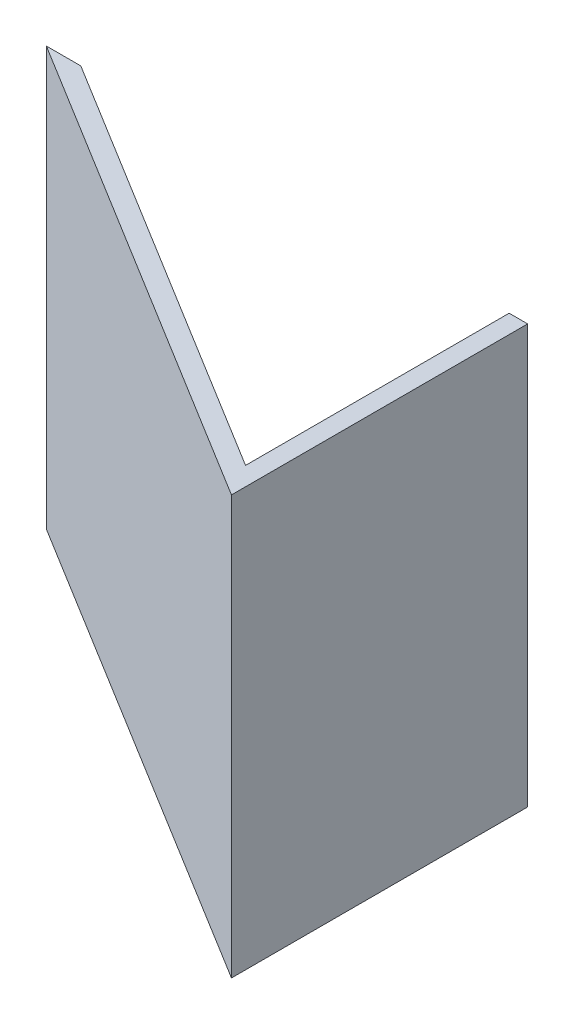
SolidWorks part; units mm, degrees
ref_plane "Front Plane" through (0, 0, 0) normal (0, 0, 1) x (1, 0, 0)
ref_plane "Top Plane" through (0, 0, 0) normal (0, 1, 0) x (1, 0, 0)
ref_plane "Right Plane" through (0, 0, 0) normal (1, 0, 0) x (0, 0, -1)
sketch "Sketch1" plane through (0, 0, 0) normal (0, 1, 0) x (1, 0, 0)
  line L1 (65.0271, 34.1908) -> (65.0271, -16.6092)
  line L4 (65.0271, 34.1908) -> (61.8521, 34.1908)
  line L17 (-17.5229, 34.1908) -> (65.0271, -16.6092)
  line L18 (61.5976, -10.8633) -> (-10.9432, 33.7772)
  line L19 (61.8521, 34.1908) -> (61.8521, -10.2592)
  line L20 (61.5976, -10.8633) -> (61.8521, -11.02)
  line L21 (61.8521, -11.02) -> (61.8521, -10.2592)
  line L22 (-10.9432, 33.7772) -> (-11.6154, 34.1908)
  line L23 (-11.6154, 34.1908) -> (-17.5229, 34.1908)
extrude "Boss-Extrude1" add sketch "Sketch1" along normal blind 71.755
